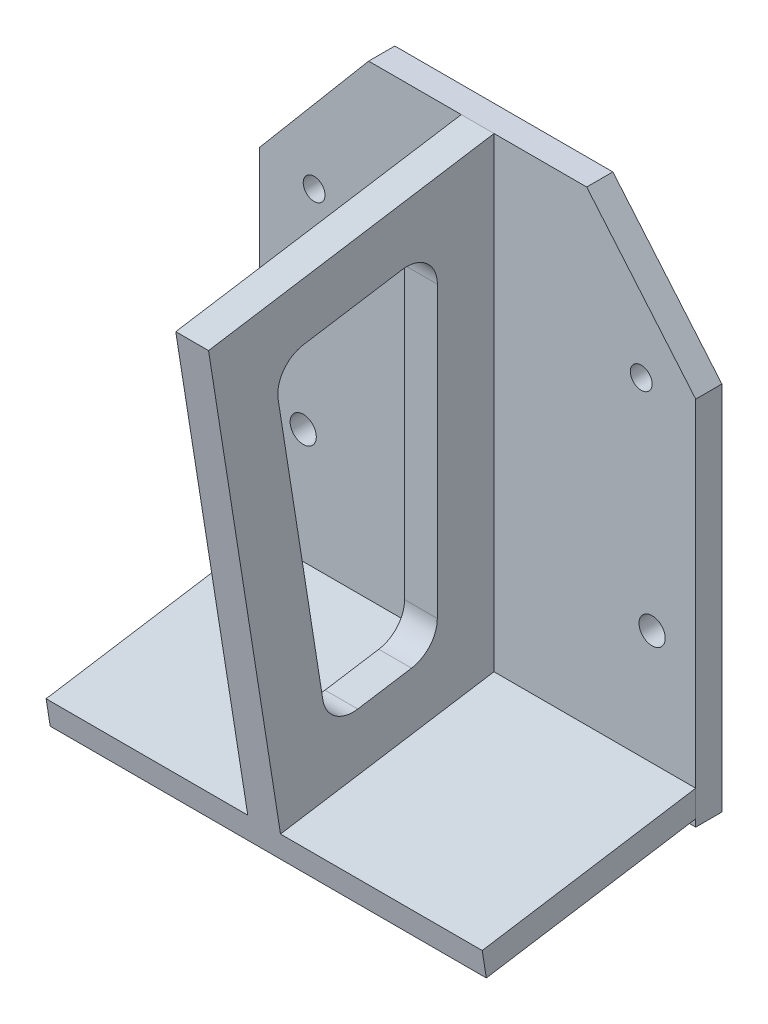
SolidWorks part; units mm, degrees
ref_plane "Front Plane" through (0, 0, 0) normal (0, 0, 1) x (1, 0, 0)
ref_plane "Top Plane" through (0, 0, 0) normal (0, 1, 0) x (1, 0, 0)
ref_plane "Right Plane" through (0, 0, 0) normal (1, 0, 0) x (0, 0, -1)
sketch "Sketch1" plane through (0, 0, 0) normal (0, 0, 1) x (1, 0, 0)
  line L0 (0, 0) -> (0, -68) construction
  line L11 (-50, -68) -> (50, -68)
  line L14 (50, -68) -> (50, 17)
  line L15 (50, 17) -> (25, 46.6204)
  line L16 (25, 46.6204) -> (-25, 46.6204)
  line L17 (-50, -68) -> (-50, 17)
  line L18 (-50, 17) -> (-25, 46.6204)
  point P9 (0, 46.6204)
  dimension "D1" = 100
  dimension "D2" = 85
  dimension "D3" = 50
  dimension "D4" = 68
extrude "Boss-Extrude1" add sketch "Sketch1" along normal blind 6
sketch "Sketch2" plane through (0, -10.1552, 64.1172) normal (0, 0.1564, -0.9877) x (-1, 0, 0)
  line L0 (190, -43.4228) -> (-190, -43.4228) construction
  line L1 (-190, -75.1728) -> (190, -75.1728) construction
  line L2 (190, -43.4228) -> (-190, -43.4228)
  line L3 (-190, -75.1728) -> (190, -75.1728)
  line L4 (-0.1819, -44.9338) -> (-0.0251, -58.5843) construction
  line L5 (-50, -67.1628) -> (-50, 16.7907) construction
  line L6 (50, -64.5843) -> (-50, -64.5843)
  line L7 (50, -64.5843) -> (50, -58.5843)
  line L8 (50, -58.5843) -> (3.7593, -58.5843)
  line L9 (-50, -64.5843) -> (-50, -58.5843)
  line L10 (50, -67.1628) -> (50, 16.7907) construction
  line L13 (-25, 46.9851) -> (25, 46.9851) construction
  line L14 (0.0091, -58.5843) -> (0, 46.9851) construction
  line L15 (-3.74, -64.5849) -> (-3.74, -64.5843)
  line L16 (-3.7593, 46.9844) -> (3.7593, 46.9851)
  line L17 (0.0091, -58.5843) -> (-0.0251, -58.5843)
  line L18 (0.0438, -64.5843) -> (0.2006, -78.2347) construction
  line L19 (-3.741, -58.5843) -> (-50, -58.5843)
  line L20 (-3.741, -58.5843) -> (-3.7593, 46.9844)
  line L22 (3.7593, -58.5843) -> (3.7593, 46.9851)
  point P9 (0.0094, -61.5843)
  dimension "D1" = 6
extrude "Boss-Extrude3" add sketch "Sketch2" along normal up to surface (48.6125 mm away) separate body contours L9 L19 L20 L16 L22 L8 L7 L6
sketch "Sketch3" plane through (-3.7593, 0, 0) normal (-1, 0, 0) x (0, 0, 1)
  line L4 (71.4672, 36.2514) -> (6, 46.6204)
  line L5 (6, 46.6204) -> (6, -60.2648)
  line L6 (6, -60.2648) -> (54.9526, -68.0182)
  line L7 (54.9526, -68.0182) -> (71.4672, 36.2514)
  line L8 (71.4672, 36.2514) -> (6, 46.6204)
  line L9 (6, 46.6204) -> (6, -60.2648)
  line L10 (6, -60.2648) -> (54.9526, -68.0182)
  line L11 (54.9526, -68.0182) -> (71.4672, 36.2514)
  line L16 (56.5937, 25.4451) -> (19, 31.3994)
  line L17 (19, 31.3994) -> (19, -49.1618)
  line L18 (19, -49.1618) -> (44.1463, -53.1446)
  line L19 (44.1463, -53.1446) -> (56.5937, 25.4451)
  line L20 (49.6798, 26.5402) -> (27.095, 30.1173)
  line L21 (19, 23.2035) -> (19, -43.1832)
  line L22 (24.905, -50.097) -> (37.2324, -52.0495)
  line L23 (45.2413, -46.2307) -> (55.4986, 18.5313)
  arc A0 (19, -43.1832) -> (24.905, -50.097) centre (26, -43.1832) ccw
  arc A1 (37.2324, -52.0495) -> (45.2413, -46.2307) centre (38.3275, -45.1357) ccw
  arc A2 (49.6798, 26.5402) -> (55.4986, 18.5313) centre (48.5848, 19.6264) cw
  arc A3 (27.095, 30.1173) -> (19, 23.2035) centre (26, 23.2035) ccw
  dimension "D3" = 7
  dimension "D1" = 0
  dimension "D2" = 13
extrude "Cut-Extrude1" cut sketch "Sketch3" along direction (1, -0.0002, 0) on the side against the normal up to surface (7.5163 mm away) contours L22 L23 L20 L21
sketch "Sketch4" plane through (0, 0, 0) normal (0, 0, -1) x (-1, 0, 0)
  line L0 (0, 0) -> (0, -68) construction
  line L1 (50, -68) -> (-50, -68) construction
  line L4 (-40, -34) -> (40, -34)
  line L5 (0, 15) -> (37.5, 15) construction
  circle A0 centre (37.5, 15) radius 2.5
  circle A1 centre (40, -34) radius 3
  circle A2 centre (-37.5, 15) radius 2.5
  circle A3 centre (-40, -34) radius 3
  point P5 (0, -34)
  dimension "D4" = 6
  dimension "D5" = 5
  dimension "D1" = 80
  dimension "D2" = 49
  dimension "D3" = 37.5
  dimension "D6" = 34
extrude "Cut-Extrude2" cut sketch "Sketch4" against normal blind 10 contours A2 | A0 | A1 | A3
